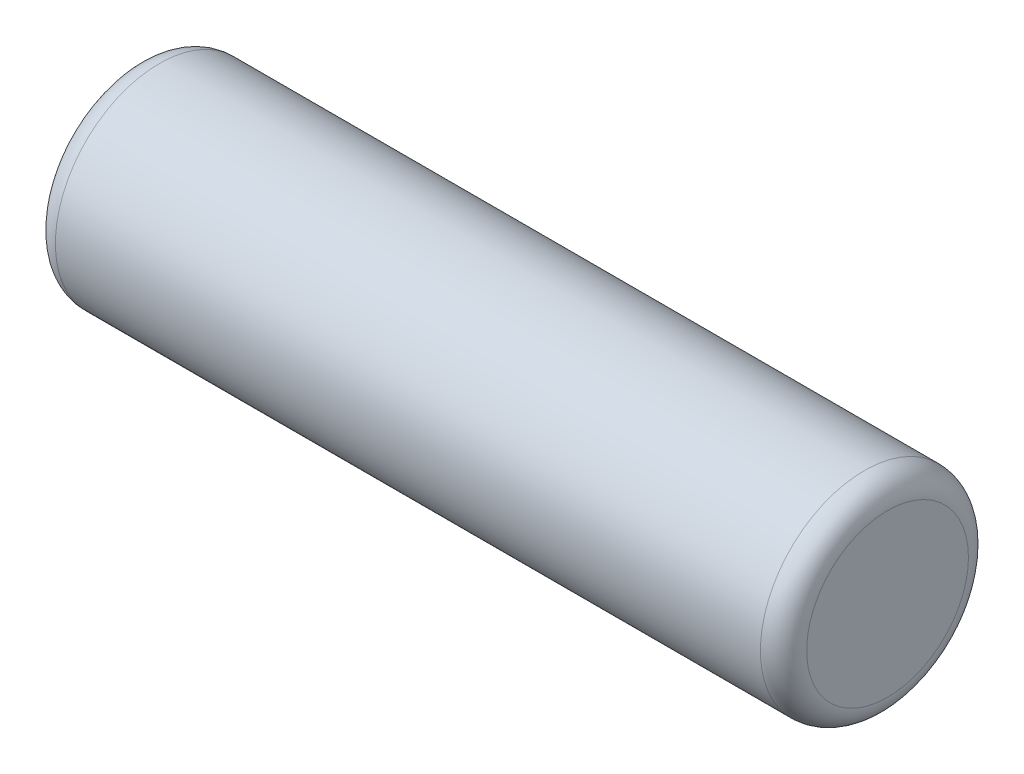
SolidWorks part; units mm, degrees
ref_plane "Front Plane" through (0, 0, 0) normal (0, 0, 1) x (1, 0, 0)
ref_plane "Top Plane" through (0, 0, 0) normal (0, 1, 0) x (1, 0, 0)
ref_plane "Right Plane" through (0, 0, 0) normal (1, 0, 0) x (0, 0, -1)
sketch "Sketch1" plane through (0, 0, 0) normal (1, 0, 0) x (0, 0, -1)
  circle A0 centre (0, 0) radius 9
  dimension "D1" = 18
extrude "Boss-Extrude1" add sketch "Sketch1" along normal blind 65
fillet "Fillet1" radius 2 2 edges at (65, 0, -9) (0, 0, -9)
